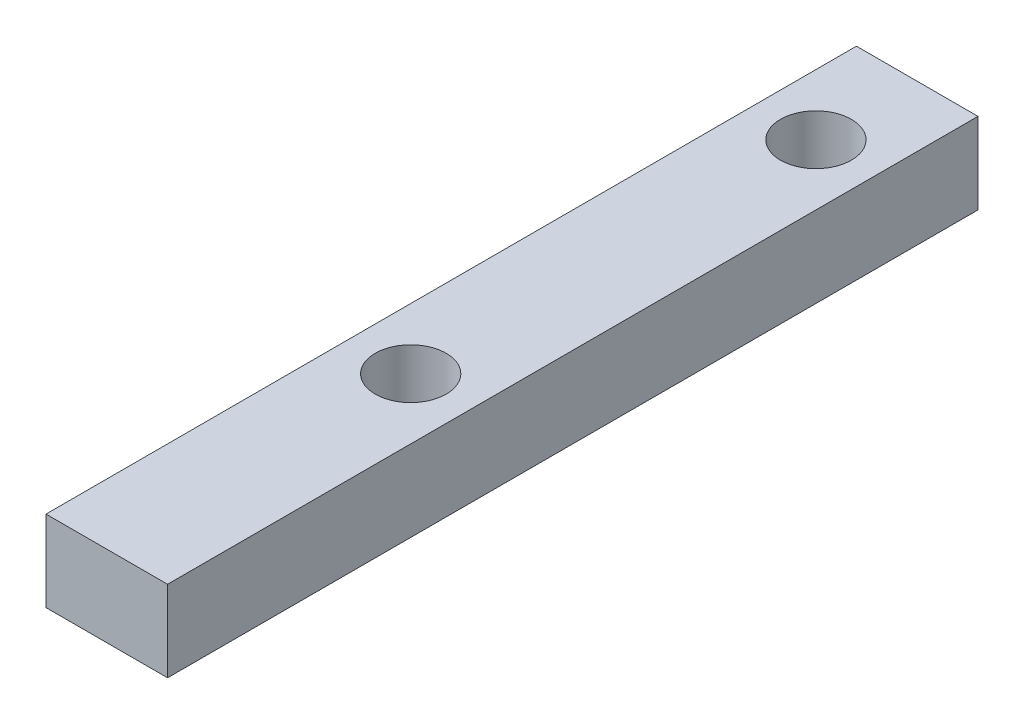
SolidWorks part; units mm, degrees
ref_plane "前视基准面" through (0, 0, 0) normal (0, 0, 1) x (1, 0, 0)
ref_plane "上视基准面" through (0, 0, 0) normal (0, 1, 0) x (1, 0, 0)
ref_plane "右视基准面" through (0, 0, 0) normal (1, 0, 0) x (0, 0, -1)
sketch "草图1" plane through (0, 0, 0) normal (0, 1, 0) x (1, 0, 0)
  line L1 (-3, 20) -> (3, 20)
  line L2 (-3, 20) -> (-3, -20)
  line L3 (-3, -20) -> (3, -20)
  line L4 (3, 20) -> (3, -20)
  line L5 (-3, 20) -> (3, -20) construction
  line L6 (-3, -20) -> (3, 20) construction
  circle A0 centre (0, 15) radius 1.75
  circle A1 centre (0, -5) radius 1.75
  point P0 (0, 0)
  point P10 (0, 0)
  point P11 (0, 0)
  dimension "D2" = 3.5
  dimension "D3" = 3.5
  dimension "D5" = 15
  dimension "D6" = 5
  dimension "D1" = 6
  dimension "D4" = 40
extrude "凸台-拉伸1" add sketch "草图1" along normal blind 4
